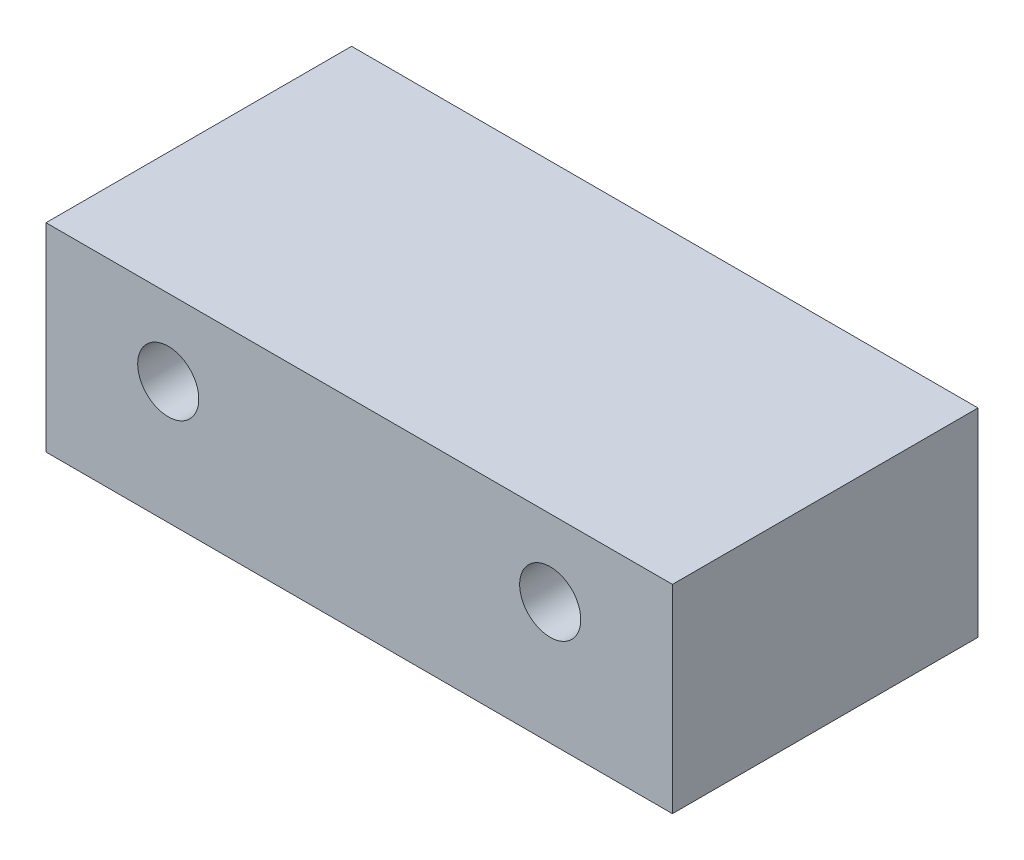
SolidWorks part; units mm, degrees
material "ABS"
ref_plane "前视基准面" through (0, 0, 0) normal (0, 0, 1) x (1, 0, 0)
ref_plane "上视基准面" through (0, 0, 0) normal (0, 1, 0) x (1, 0, 0)
ref_plane "右视基准面" through (0, 0, 0) normal (1, 0, 0) x (0, 0, -1)
other "Configuration Table"
sketch "草图1" plane through (0, 0, 0) normal (0, 0, 1) x (1, 0, 0)
  line L0 (0, 0) -> (12.5, 0) construction
  line L1 (-20.5, -5) -> (20.5, -5)
  line L2 (-20.5, -5) -> (-20.5, 5)
  line L3 (-20.5, 5) -> (20.5, 5)
  line L4 (20.5, -5) -> (20.5, 5)
  line L5 (-20.5, -5) -> (20.5, 5) construction
  line L6 (-20.5, 5) -> (20.5, -5) construction
  line L7 (0, 0) -> (0, 8.8) construction
  circle A0 centre (12.5, 0) radius 2
  circle A1 centre (-12.5, 0) radius 2
  point P0 (0, 0)
  dimension "D3" = 4
  dimension "D1" = 10
  dimension "D2" = 8
  dimension "D4" = 12.5
extrude "凸台-拉伸1" add sketch "草图1" along normal blind 20
sketch "草图2" plane through (0, 0, 20) normal (0, 0, 1) x (1, 0, 0)
  line L0 (20.5, -5) -> (20.5, 5) construction
  line L1 (-20.5, -5) -> (20.5, -5)
  line L2 (-20.5, -5) -> (-20.5, -8)
  line L3 (-20.5, -8) -> (20.5, -8)
  line L4 (20.5, -5) -> (20.5, -8)
  dimension "D1" = 3
extrude "凸台-拉伸2" add sketch "草图2" against normal up to surface (20 mm away) up to face at (14.5, 0, 0)
